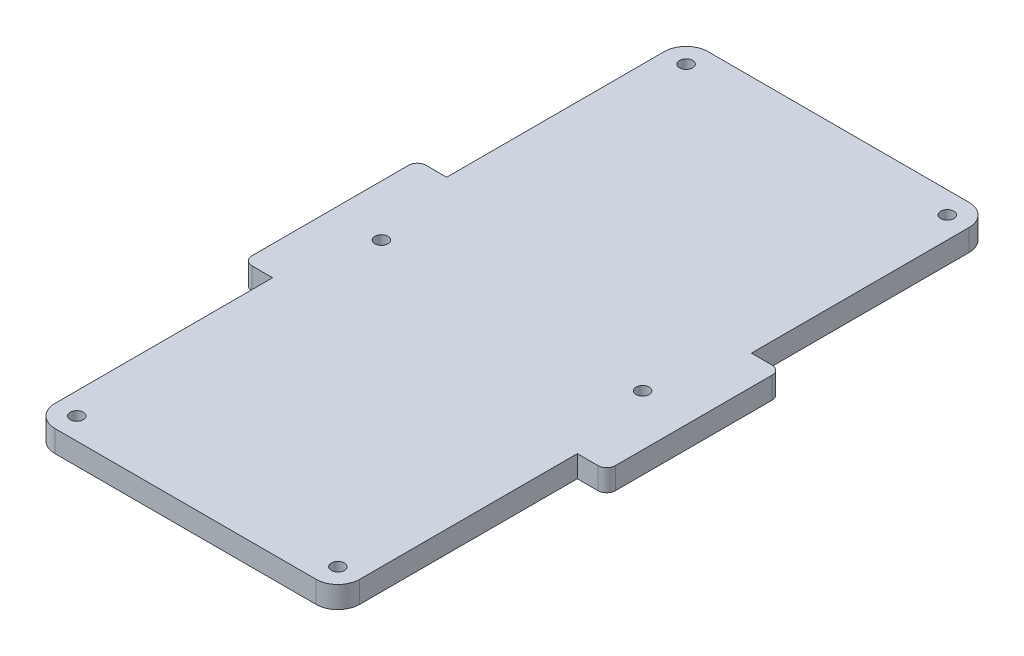
SolidWorks part; units mm, degrees
material "PMMA"
ref_plane "前视基准面" through (0, 0, 0) normal (0, 0, 1) x (1, 0, 0)
ref_plane "上视基准面" through (0, 0, 0) normal (0, 1, 0) x (1, 0, 0)
ref_plane "右视基准面" through (0, 0, 0) normal (1, 0, 0) x (0, 0, -1)
sketch "草图1" plane through (0, 0, 0) normal (0, 1, 0) x (1, 0, 0)
  line L0 (-30.9298, -28.8406) -> (39.0702, -28.8406) construction
  line L1 (-25.9298, 46.1594) -> (34.0702, 46.1594)
  line L2 (-30.9298, 41.1594) -> (-30.9298, -8.8406)
  line L3 (-25.9298, -103.8406) -> (34.0702, -103.8406)
  line L4 (39.0702, 41.1594) -> (39.0702, -8.8406)
  line L5 (-30.9298, 46.1594) -> (39.0702, -103.8406) construction
  line L6 (-30.9298, -103.8406) -> (39.0702, 46.1594) construction
  line L7 (4.0702, 46.1594) -> (4.0702, -103.8406) construction
  line L8 (-37.6798, -10.8406) -> (-37.6798, -46.8406)
  line L9 (-35.6798, -8.8406) -> (-30.9298, -8.8406)
  line L10 (-35.6798, -48.8406) -> (-30.9298, -48.8406)
  line L11 (43.8202, -48.8406) -> (39.0702, -48.8406)
  line L12 (45.8202, -10.8406) -> (45.8202, -46.8406)
  line L13 (43.8202, -8.8406) -> (39.0702, -8.8406)
  line L14 (-30.9298, -48.8406) -> (-30.9298, -98.8406)
  line L15 (39.0702, -48.8406) -> (39.0702, -98.8406)
  arc A0 (-30.9298, -98.8406) -> (-25.9298, -103.8406) centre (-25.9298, -98.8406) ccw
  arc A1 (34.0702, -103.8406) -> (39.0702, -98.8406) centre (34.0702, -98.8406) ccw
  arc A2 (39.0702, 41.1594) -> (34.0702, 46.1594) centre (34.0702, 41.1594) ccw
  arc A3 (-30.9298, 41.1594) -> (-25.9298, 46.1594) centre (-25.9298, 41.1594) cw
  arc A4 (45.8202, -46.8406) -> (43.8202, -48.8406) centre (43.8202, -46.8406) cw
  arc A5 (45.8202, -10.8406) -> (43.8202, -8.8406) centre (43.8202, -10.8406) ccw
  arc A6 (-35.6798, -48.8406) -> (-37.6798, -46.8406) centre (-35.6798, -46.8406) cw
  arc A7 (-37.6798, -10.8406) -> (-35.6798, -8.8406) centre (-35.6798, -10.8406) cw
  point P4 (4.0702, -28.8406)
  point P12 (-37.6798, -28.8406)
  point P32 (45.8202, -48.8406)
  point P35 (45.8202, -8.8406)
  point P38 (-37.6798, -48.8406)
  point P41 (-37.6798, -8.8406)
  dimension "D4" = 5
  dimension "D5" = 2
  dimension "D1" = 70
  dimension "D2" = 150
  dimension "D3" = 6.75
extrude "凸台-拉伸1" add sketch "草图1" along normal blind 5
sketch "草图3" plane through (0, 5, 0) normal (0, 1, 0) x (1, 0, 0)
  circle A0 centre (34.0702, 41.1594) radius 1.5
  circle A1 centre (-25.9298, 41.1594) radius 1.5
  circle A2 centre (-25.9298, -98.8406) radius 1.5
  circle A3 centre (34.0702, -98.8406) radius 1.5
  circle A4 centre (34.0702, -28.8406) radius 1.5
  circle A5 centre (-25.9298, -28.8406) radius 1.5
extrude "切除-拉伸1" cut sketch "草图3" against normal through all
